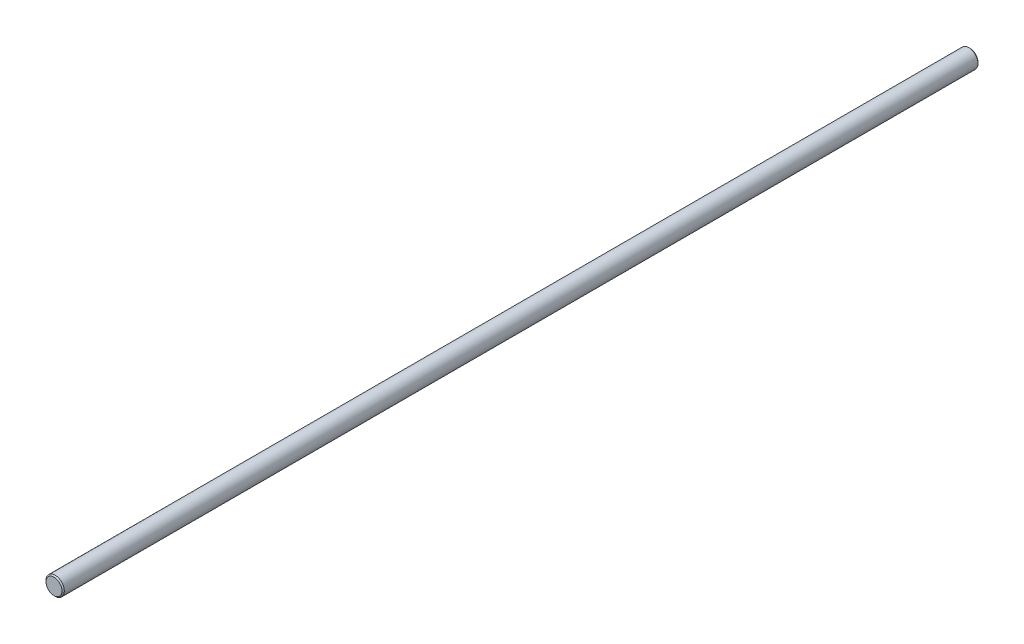
SolidWorks part; units mm, degrees
ref_plane "Front Plane" through (0, 0, 0) normal (0, 0, 1) x (1, 0, 0)
ref_plane "Top Plane" through (0, 0, 0) normal (0, 1, 0) x (1, 0, 0)
ref_plane "Right Plane" through (0, 0, 0) normal (1, 0, 0) x (0, 0, -1)
sketch "Sketch2" plane through (0, 0, 0) normal (0, 0, 1) x (1, 0, 0)
  circle A0 centre (0, 0) radius 6
  dimension "D1" = 12
extrude "Boss-Extrude1" add sketch "Sketch2" along normal mid plane 600
chamfer "Chamfer1" distance 0.75 angle 45 2 edges at (6, 0, -300) (6, 0, 300)
